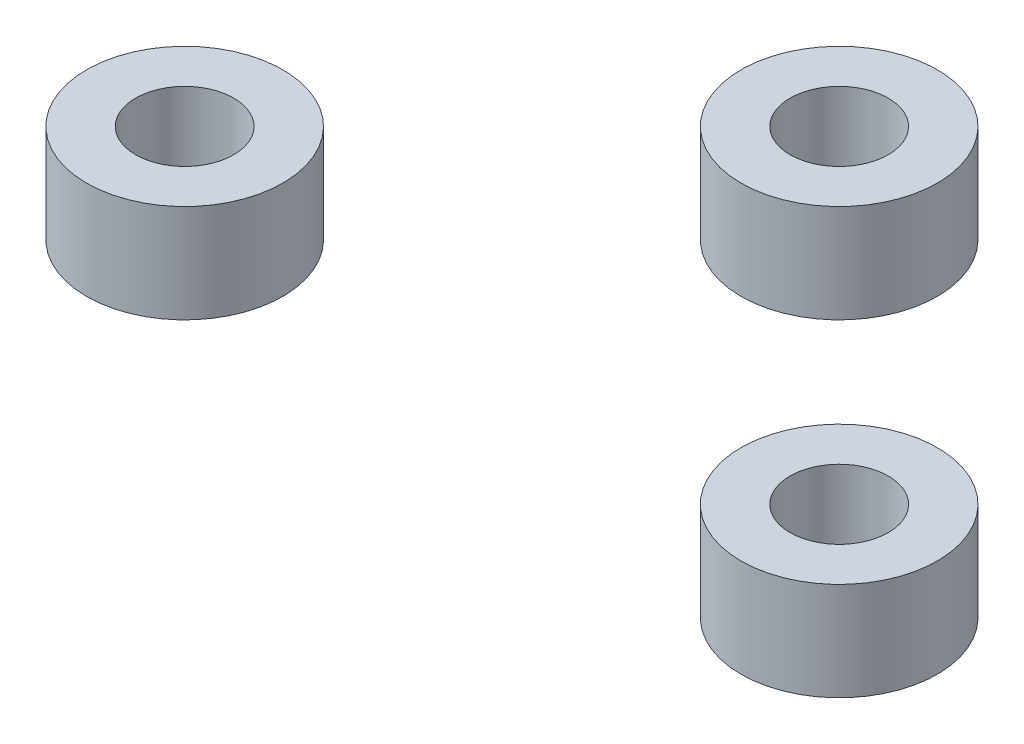
SolidWorks part; units mm, degrees
ref_plane "Front Plane" through (0, 0, 0) normal (0, 0, 1) x (1, 0, 0)
ref_plane "Top Plane" through (0, 0, 0) normal (0, 1, 0) x (1, 0, 0)
ref_plane "Right Plane" through (0, 0, 0) normal (1, 0, 0) x (0, 0, -1)
sketch "Sketch1" plane through (0, 0, 0) normal (0, 1, 0) x (1, 0, 0)
  line L0 (78.3985, 120.8249) -> (-23.6439, 18.7825)
  line L1 (122.5931, 119.8333) -> (221.2132, 21.2132)
  line L2 (0, -30) -> (200, -30)
  line L3 (-23.6439, 18.7825) -> (78.3985, 120.8249)
  line L4 (200, -30) -> (0, -30)
  line L5 (221.2132, 21.2132) -> (122.5931, 119.8333)
  circle A0 centre (0, 0) radius 15
  circle A1 centre (0, 0) radius 30
  circle A2 centre (100, 100) radius 15
  circle A3 centre (100, 100) radius 30
  circle A4 centre (200, 0) radius 15
  circle A5 centre (200, 0) radius 30
  circle A6 centre (100, 100) radius 30
  circle A7 centre (0, 0) radius 30
  circle A8 centre (200, 0) radius 30
  dimension "D1" = 60
  dimension "D2" = 60
  dimension "D3" = 30
  dimension "D4" = 60
  dimension "D5" = 30
  dimension "D6" = 30
  dimension "D7" = 200
  dimension "D8" = 100
  dimension "D9" = 100
  dimension "D10" = 100
extrude "Boss-Extrude1" add sketch "Sketch1" along normal blind 30 contours A5 A4 | A3 A2 | A1 A0
